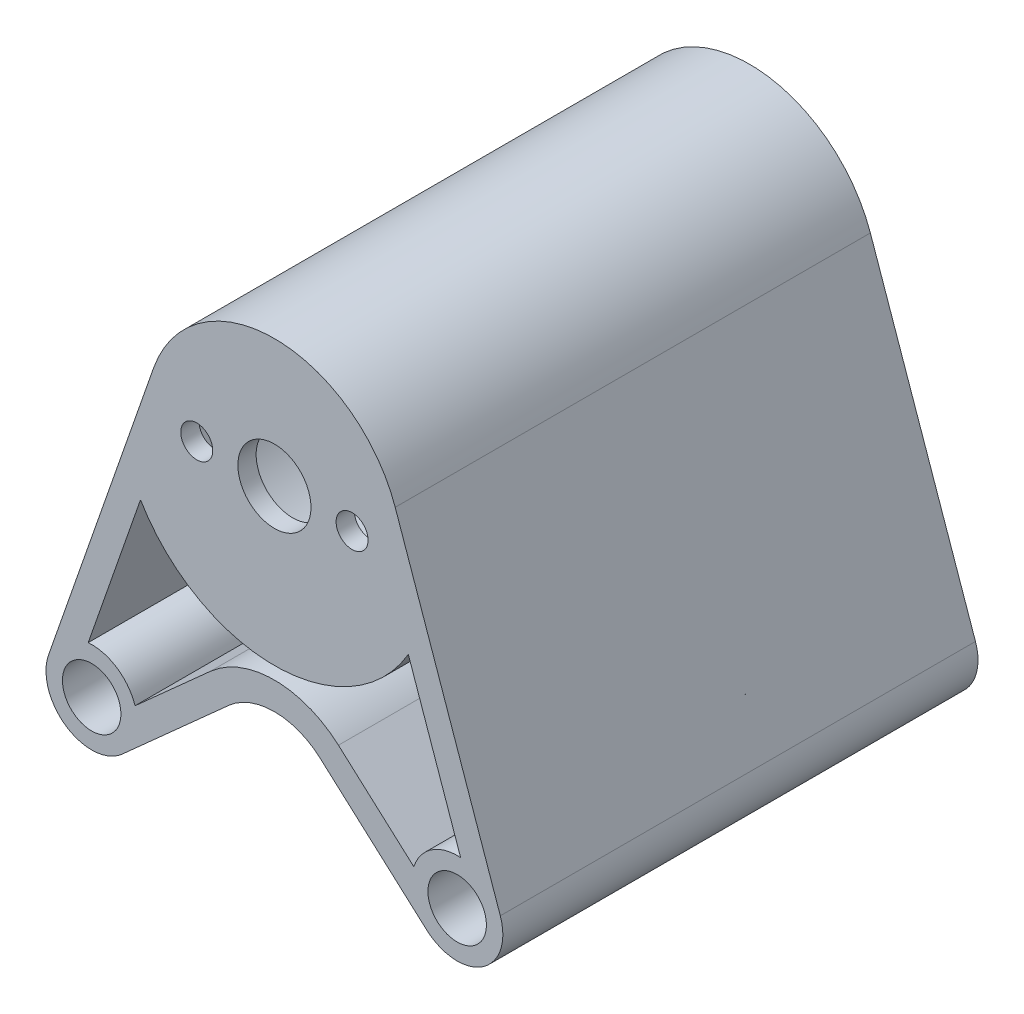
SolidWorks part; units mm, degrees
ref_plane "Front Plane" through (0, 0, 0) normal (0, 0, 1) x (1, 0, 0)
ref_plane "Top Plane" through (0, 0, 0) normal (0, 1, 0) x (1, 0, 0)
ref_plane "Right Plane" through (0, 0, 0) normal (1, 0, 0) x (0, 0, -1)
sketch "Sketch3" plane through (0, 0, 0) normal (0, 0, 1) x (1, 0, 0)
  circle A0 centre (8.5, 0) radius 1.75
  circle A1 centre (-8.5, 0) radius 1.75
  circle A2 centre (0, 0) radius 14
  circle A3 centre (0, 0) radius 12.65
  circle A4 centre (0, 0) radius 4
  circle M1 centre (8.5, 0) radius 1.5
  circle M2 centre (0, 0) radius 3.5
  circle M3 centre (0, 0) radius 12.5
  circle M4 centre (-8.5, 0) radius 1.5
  dimension "D1" = 28
  dimension "D2" = 25.3
  dimension "D3" = 8
  dimension "D4" = 3.5
  dimension "D5" = 3.5
extrude "Boss-Extrude1" add sketch "Sketch3" along normal blind 2 contours M3 M2 M4 M1 | A3 M3 | A2 A3
sketch "Sketch4" plane through (0, 0, 0) normal (0, 0, -1) x (-1, 0, 0)
  circle A0 centre (0, 0) radius 14
  circle A1 centre (0, 0) radius 12.65
  dimension "D1" = 25.3
extrude "Boss-Extrude2" add sketch "Sketch4" along normal blind 50
sketch "Sketch5" plane through (0, 0, 2) normal (0, 0, 1) x (1, 0, 0)
  line L0 (13.2184, 4.6123) -> (24.7209, -28.3528)
  line L1 (5.0044, -23.2793) -> (16.6637, -33.7242)
  line L2 (-13.2184, 4.6123) -> (-24.7209, -28.3528)
  line L3 (-5.0044, -23.2793) -> (-16.6637, -33.7242)
  line L4 (14.6561, -8.6139) -> (20.3786, -25.0144)
  line L5 (7.0061, -21.0448) -> (15.2522, -28.4319)
  line L6 (-7.0061, -21.0448) -> (-15.2522, -28.4319)
  line L7 (-14.6561, -8.6139) -> (-20.3786, -25.0144)
  line L8 (-7.0061, -21.0448) -> (-18.6655, -31.4897) construction
  line L9 (-14.6561, -8.6139) -> (-21.8883, -29.3411) construction
  line L10 (7.0061, -21.0448) -> (18.6655, -31.4897) construction
  line L11 (14.6561, -8.6139) -> (21.8883, -29.3411) construction
  arc A0 (16.6637, -33.7242) -> (24.7209, -28.3528) centre (20, -30) ccw
  arc A1 (-24.7209, -28.3528) -> (-16.6637, -33.7242) centre (-20, -30) ccw
  circle A2 centre (0, 0) radius 14 construction
  arc A3 (-13.2184, 4.6123) -> (13.2184, 4.6123) centre (0, 0) ccw
  arc A4 (5.0044, -23.2793) -> (-5.0044, -23.2793) centre (0, -28.8655) ccw
  arc A6 (7.0061, -21.0448) -> (-7.0061, -21.0448) centre (0, -28.8655) ccw
  arc A8 (-14.6561, -8.6139) -> (14.6561, -8.6139) centre (0, 0) ccw
  circle A9 centre (20, -30) radius 3
  circle A10 centre (-20, -30) radius 3
  arc A11 (-21.8883, -29.3411) -> (-18.6655, -31.4897) centre (-20, -30) ccw construction
  circle A12 centre (-20, -30) radius 5
  circle A13 centre (20, -30) radius 5
  arc A14 (18.6655, -31.4897) -> (21.8883, -29.3411) centre (20, -30) ccw construction
  circle M4 centre (0, 0) radius 14
  dimension "D1" = 10
  dimension "D2" = 10
  dimension "D3" = 15
  dimension "D5" = 6
  dimension "D6" = 6
  dimension "D4" = 3
extrude "Boss-Extrude3" add sketch "Sketch5" against normal up to surface (52 mm away) contours A13 L0 L2 A12 L7 A8 L4 M4 | A13 L5 A6 L6 A12 L3 A4 L1 | A12 A1 A10 | A0 A13 A9 up to face at (-14, 0, -50)
sketch "Sketch6" plane through (0, 0, -50) normal (0, 0, -1) x (-1, 0, 0)
  circle A2 centre (0, 0) radius 13.15
  circle A3 centre (0, 0) radius 13.15
  dimension "D1" = 0.5
extrude "Cut-Extrude1" cut sketch "Sketch6" against normal up to surface (50 mm away) up to face at (10.25, 0, 0)
sketch "Sketch8" plane through (0, 0, -50) normal (0, 0, -1) x (-1, 0, 0)
  circle A1 centre (20, -30) radius 3 construction
  circle A9 centre (20, -30) radius 3
  circle A10 centre (-20, -30) radius 3 construction
  circle A11 centre (-20, -30) radius 3
  circle A12 centre (-20, -30) radius 3.2
  circle A13 centre (20, -30) radius 3.2
  circle M11 centre (-20, -30) radius 3
  circle M20 centre (20, -30) radius 3
  dimension "D1" = 0.2
extrude "Cut-Extrude2" cut sketch "Sketch8" against normal up to surface (52 mm away) contours A13 M20 | A12 M11 | A9 | A11
